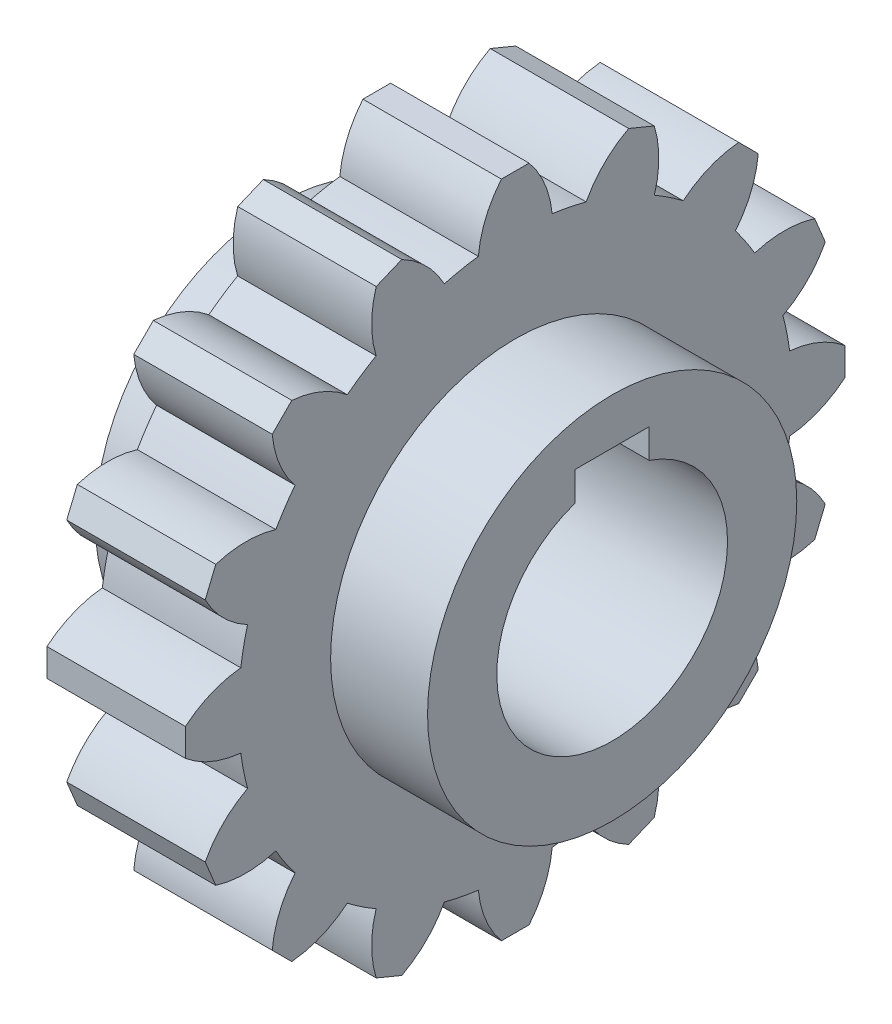
SolidWorks part; units mm, degrees
ref_plane "Front Plane" through (0, 0, 0) normal (0, 0, 1) x (1, 0, 0)
ref_plane "Top Plane" through (0, 0, 0) normal (0, 1, 0) x (1, 0, 0)
ref_plane "Right Plane" through (0, 0, 0) normal (1, 0, 0) x (0, 0, -1)
sketch "Sketch1" plane through (0, 0, 0) normal (1, 0, 0) x (0, 0, -1)
  circle A0 centre (0, 0) radius 30
  dimension "D1" = 30
extrude "Boss-Extrude1" add sketch "Sketch1" along normal mid plane 15
sketch "Sketch2" plane through (7.5, 0, 0) normal (1, 0, 0) x (0, 0, -1)
  line L0 (0, 0) -> (0, 35.7321) construction
  line L1 (1.5, 35.7321) -> (-1.5, 35.7321)
  arc A0 (-4, 29.7321) -> (4, 29.7321) centre (0, 0) cw
  circle A1 centre (0, 0) radius 30 construction
  arc A2 (-1.5, 35.7321) -> (-4, 29.7321) centre (6.9505, 28.6902) ccw
  arc A3 (1.5, 35.7321) -> (4, 29.7321) centre (-6.9505, 28.6902) cw
  dimension "D1" = 1.5
  dimension "D3" = 6
  dimension "D4" = 11
  dimension "D2" = 4
extrude "Boss-Extrude2" add sketch "Sketch2" against normal up to surface (15 mm away) up to face at (-7.5, 0, -30)
pattern_circular "CirPattern1" count 16 over 360 about axis through (0, 0, 0) along (1, 0, 0) of "Boss-Extrude2"
sketch "Sketch3" plane through (0, 0, 0) normal (1, 0, 0) x (0, 0, -1)
  circle A0 centre (0, 0) radius 20
  dimension "D1" = 40
extrude "Boss-Extrude3" add sketch "Sketch3" along normal mid plane 36
sketch "Sketch4" plane through (18, 0, 0) normal (1, 0, 0) x (0, 0, -1)
  line L0 (0, 0) -> (0, 15) construction
  line L1 (-4, 15) -> (4, 15)
  line L2 (-4, 15) -> (-4, 11.8427)
  line L3 (4, 15) -> (4, 11.8427)
  arc A0 (-4, 11.8427) -> (4, 11.8427) centre (0, 0) ccw
  dimension "D1" = 25
  dimension "D2" = 8
  dimension "D3" = 15
extrude "Cut-Extrude1" cut sketch "Sketch4" against normal through all
